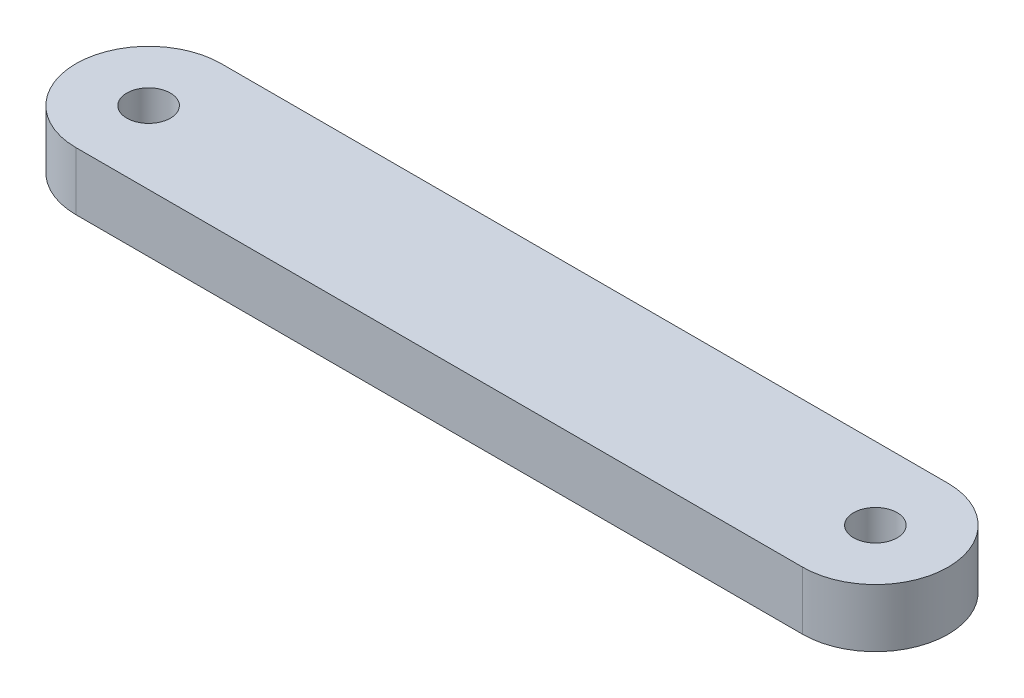
SolidWorks part; units mm, degrees
ref_plane "前视基准面" through (0, 0, 0) normal (0, 0, 1) x (1, 0, 0)
ref_plane "上视基准面" through (0, 0, 0) normal (0, 1, 0) x (1, 0, 0)
ref_plane "右视基准面" through (0, 0, 0) normal (1, 0, 0) x (0, 0, -1)
sketch "草图1" plane through (0, 0, 0) normal (0, 1, 0) x (1, 0, 0)
  line L0 (-26.2524, 0) -> (23.7476, 0) construction
  line L1 (-26.2524, 5) -> (23.7476, 5)
  line L2 (-26.2524, -5) -> (23.7476, -5)
  arc A0 (-26.2524, 5) -> (-26.2524, -5) centre (-26.2524, 0) ccw
  arc A1 (23.7476, -5) -> (23.7476, 5) centre (23.7476, 0) ccw
  circle A2 centre (-26.2524, 0) radius 1.5
  circle A3 centre (23.7476, 0) radius 1.5
  point P3 (-1.2524, 0)
  dimension "10" = 5
  dimension "D1" = 50
extrude "凸台-拉伸1" add sketch "草图1" along normal blind 4
